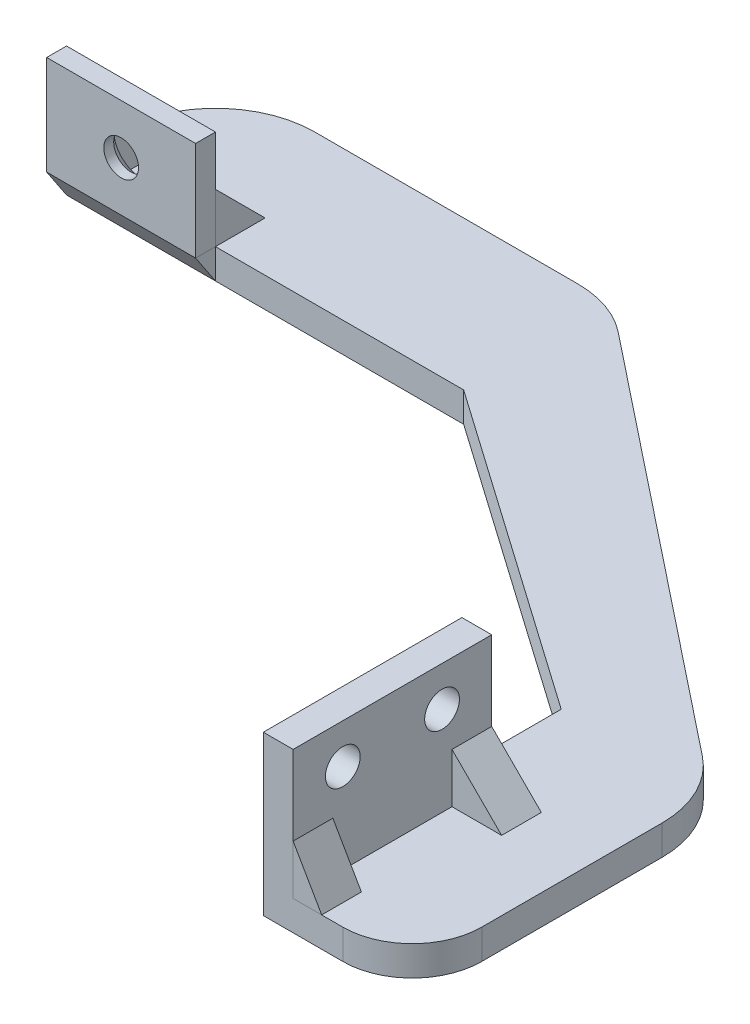
SolidWorks part; units mm, degrees
ref_plane "Front Plane" through (0, 0, 0) normal (0, 0, 1) x (1, 0, 0)
ref_plane "Top Plane" through (0, 0, 0) normal (0, 1, 0) x (1, 0, 0)
ref_plane "Right Plane" through (0, 0, 0) normal (1, 0, 0) x (0, 0, -1)
sketch "Base" plane through (0, 0, 0) normal (0, 1, 0) x (1, 0, 0)
  line L0 (20, 7.5) -> (67.7661, -30.4431)
  line L1 (20, -7.5) -> (-20, -7.5)
  line L3 (20, 7.5) -> (-20, 7.5)
  line L4 (-20, -7.5) -> (-20, 7.5)
  line L5 (20, -7.5) -> (-20, 7.5) construction
  line L6 (20, 7.5) -> (-20, -7.5) construction
  line L8 (52.7661, -30.4431) -> (20, -7.5)
  line L10 (52.7661, -30.4431) -> (52.7661, -60.4431)
  line L11 (52.7661, -60.4431) -> (67.7661, -60.4431)
  line L12 (67.7661, -30.4431) -> (67.7661, -60.4431)
  point P0 (0, 0)
  dimension "D1" = 15
  dimension "D2" = 40
  dimension "D3" = 40
  dimension "D4" = 145
  dimension "D5" = 30
extrude "Base EXT" add sketch "Base" along normal blind 3
sketch "Mounting Plate" plane through (0, 3, 0) normal (0, 1, 0) x (1, 0, 0)
  line L2 (-20, -7.5) -> (-5, -7.5)
  line L3 (-20, -7.5) -> (-20, -9.5)
  line L4 (-20, -9.5) -> (-5, -9.5)
  line L7 (-5, -7.5) -> (-5, -9.5)
  dimension "D1" = 2
  dimension "D2" = 15
extrude "LED Box Plate EXT" add sketch "Mounting Plate" along normal blind 10
sketch "Sketch16" plane through (-20, 0, 0) normal (-1, 0, 0) x (0, 0, 1)
  line L0 (2.5, 3) -> (7.5, 8)
  line L1 (-7.5, 3) -> (7.5, 3) construction
  line L2 (7.5, 13) -> (7.5, 3) construction
  line L3 (2.5, 3) -> (7.5, 3)
  line L4 (7.5, 3) -> (7.5, 8)
  dimension "D1" = 5
  dimension "D2" = 5
extrude "Boss-Extrude6" add sketch "Sketch16" against normal blind 4 separate body
sketch "Sketch17" plane through (-5, 0, 0) normal (1, 0, 0) x (0, 0, -1)
  line L0 (-7.5, 8) -> (-2.5, 3)
  line L3 (-7.5, 13) -> (-7.5, 3) construction
  line L4 (-2.5, 3) -> (-7.5, 3)
  line L5 (-7.5, 3) -> (-7.5, 8)
  line L7 (-2.5, 3) -> (-7.5, 3) construction
  dimension "D1" = 5
extrude "Boss-Extrude9" add sketch "Sketch17" against normal blind 4
sketch "Sketch18" plane through (-20, 0, 0) normal (-1, 0, 0) x (0, 0, 1)
  line L0 (7.5, 0) -> (9.5, 3)
  line L1 (9.5, 3) -> (7.5, 3)
  line L2 (7.5, 3) -> (7.5, 0)
extrude "Boss-Extrude11" add sketch "Sketch18" against normal up to surface (15 mm away) separate body up to face at (-5, 8, 8.5)
sketch "M3 Screw" plane through (0, 0, 7.5) normal (0, 0, -1) x (-1, 0, 0)
  line L2 (5, 13) -> (20, 13) construction
  line L3 (12.5, 13) -> (12.5, 3) construction
  line L4 (5, 3) -> (20, 3) construction
  circle A0 centre (12.5, 8) radius 1.75
  dimension "D1" = 3.5
extrude "Cut-Extrude3" cut sketch "M3 Screw" against normal through all
sketch "Sketch13" plane through (0, 3, 0) normal (0, 1, 0) x (1, 0, 0)
  line L1 (52.7661, -60.4431) -> (55.7661, -60.4431)
  line L2 (52.7661, -60.4431) -> (52.7661, -40.4431)
  line L3 (52.7661, -40.4431) -> (55.7661, -40.4431)
  line L4 (55.7661, -60.4431) -> (55.7661, -40.4431)
  dimension "D1" = 20
  dimension "D2" = 3
extrude "Mount Plate BOX EXT" add sketch "Sketch13" along normal blind 13
sketch "Sketch20" plane through (0, 0, 60.4431) normal (0, 0, 1) x (1, 0, 0)
  line L0 (55.7661, 8) -> (58.6418, 3)
  line L1 (55.7661, 16) -> (55.7661, 3) construction
  line L2 (55.7661, 3) -> (67.7661, 3) construction
  line L3 (55.7661, 8) -> (55.7661, 3)
  line L4 (55.7661, 3) -> (58.6418, 3)
extrude "Boss-Extrude12" add sketch "Sketch20" against normal blind 4 separate body
sketch "Sketch21" plane through (0, 0, 40.4431) normal (0, 0, -1) x (-1, 0, 0)
  line L0 (-55.7661, 8) -> (-60.7661, 3)
  line L1 (-55.7661, 16) -> (-55.7661, 3) construction
  line L2 (-60.7661, 3) -> (-55.7661, 3)
  line L3 (-55.7661, 3) -> (-55.7661, 8)
  line L4 (-55.7661, 3) -> (-58.6418, 3) construction
  dimension "D1" = 5
  dimension "D2" = 5
extrude "Boss-Extrude15" add sketch "Sketch21" against normal blind 4
sketch "M3 Screws" plane through (55.7661, 0, 0) normal (1, 0, 0) x (0, 0, -1)
  line L0 (-50.4431, 16) -> (-50.4431, 3) construction
  line L1 (-60.4431, 16) -> (-40.4431, 16) construction
  line L2 (-60.4431, 3) -> (-44.4431, 3) construction
  circle A0 centre (-55.4431, 12) radius 1.75
  circle A1 centre (-45.4431, 12) radius 1.75
  dimension "D1" = 3.5
  dimension "D2" = 4
  dimension "D3" = 5
extrude "M3 Screw Cut" cut sketch "M3 Screws" against normal blind 8
fillet "Fillet1" radius 10 1 edges at (-20, 1.5, -7.5)
fillet "Fillet2" radius 7 1 edges at (67.7661, 1.5, 60.4431)
fillet "Fillet3" radius 10 1 edges at (67.7661, 1.5, 30.4431)
fillet "Fillet4" radius 10 1 edges at (20, 1.5, -7.5)
sketch "M3 Screw Head" plane through (0, 0, 7.5) normal (0, 0, -1) x (-1, 0, 0)
  circle A0 centre (12.5, 8) radius 2.75
  dimension "D1" = 5.5
extrude "Cut-Extrude4" cut sketch "M3 Screw Head" against normal blind 10 draft 45
